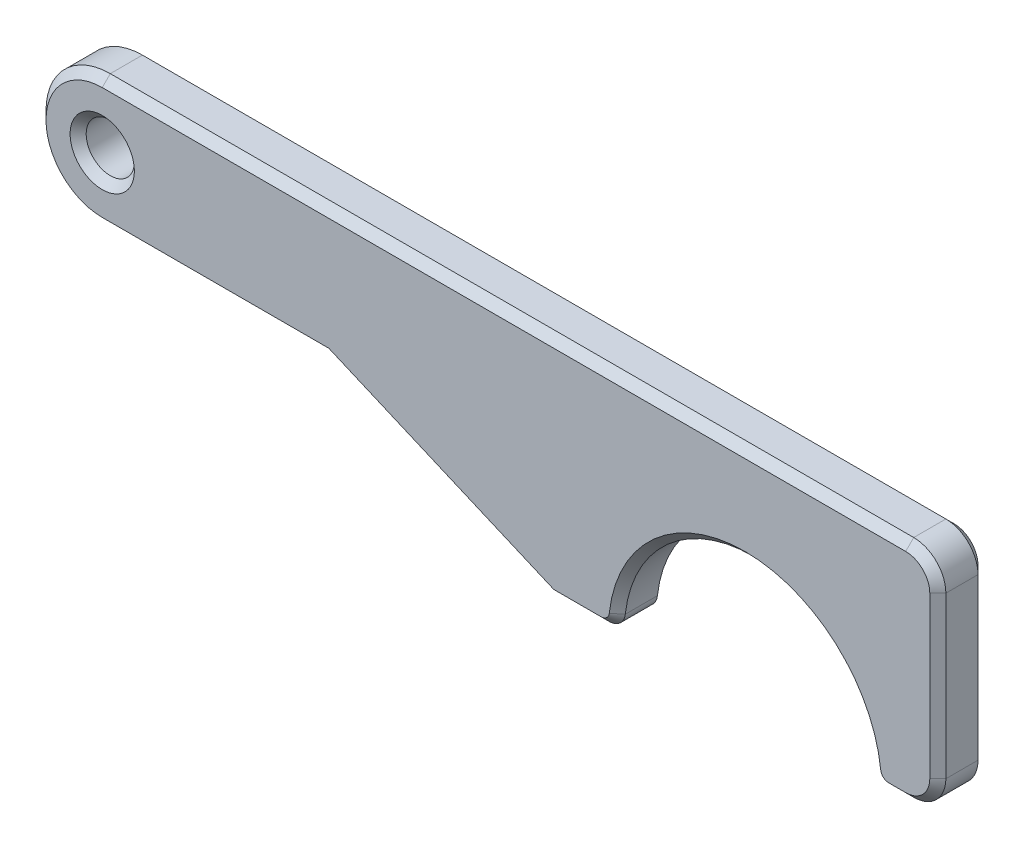
SolidWorks part; units mm, degrees
material "6061-T6 (SS)"
ref_plane "Front Plane" through (0, 0, 0) normal (0, 0, 1) x (1, 0, 0)
ref_plane "Top Plane" through (0, 0, 0) normal (0, 1, 0) x (1, 0, 0)
ref_plane "Right Plane" through (0, 0, 0) normal (1, 0, 0) x (0, 0, -1)
sketch "Sketch1" plane through (0, 0, 0) normal (0, 0, 1) x (1, 0, 0)
  line L0 (0, 12.7) -> (165.1, 12.7)
  line L1 (0, -12.7) -> (44.45, -12.7)
  line L2 (44.45, -12.7) -> (88.9, -31.75)
  line L3 (165.1, 12.7) -> (165.1, -31.75)
  line L4 (165.1, -31.75) -> (152.4, -31.75)
  line L5 (88.9, -31.75) -> (101.6, -31.75)
  circle A0 centre (0, 0) radius 4.7625
  circle A1 centre (0, 0) radius 12.7
  circle A2 centre (127, -31.75) radius 25.4
  dimension "D1" = 25.4
  dimension "D2" = 9.525
  dimension "D3" = 50.8
  dimension "D4" = 127
  dimension "D5" = 12.7
  dimension "D6" = 31.75
  dimension "D7" = 44.45
extrude "Boss-Extrude1" add sketch "Sketch1" along normal blind 9.525 contours A2 L4 L3 L0 A1 L1 L2 L5 | A1 A0
fillet "Fillet1" radius 6.35 2 edges at (165.1, -31.75, 4.7625) (165.1, 12.7, 4.7625)
fillet "Fillet2" radius 3.175 2 edges at (152.4, -31.75, 4.7625) (101.6, -31.75, 4.7625)
chamfer "Chamfer1" distance 1.5875 angle 45 26 edges at (4.7625, 0, 0) (157.074, -31.75, 0) (165.1, -9.525, 0) (79.375, 12.7, 0) (-12.7, 0, 0) (22.225, -12.7, 0) (66.675, -22.225, 0) (93.751, -31.75, 0) (127, -6.35, 0) (4.7625, 0, 9.525) (93.751, -31.75, 9.525) (66.675, -22.225, 9.525) (22.225, -12.7, 9.525) (-12.7, 0, 9.525) (79.375, 12.7, 9.525) (165.1, -9.525, 9.525) (157.074, -31.75, 9.525) (127, -6.35, 9.525) (163.2401, 10.8401, 0) (163.2401, -29.8901, 0) (163.2401, 10.8401, 9.525) (163.2401, -29.8901, 9.525) (100.7186, -30.9415, 0) (153.2814, -30.9415, 0) (100.7186, -30.9415, 9.525) (153.2814, -30.9415, 9.525)
